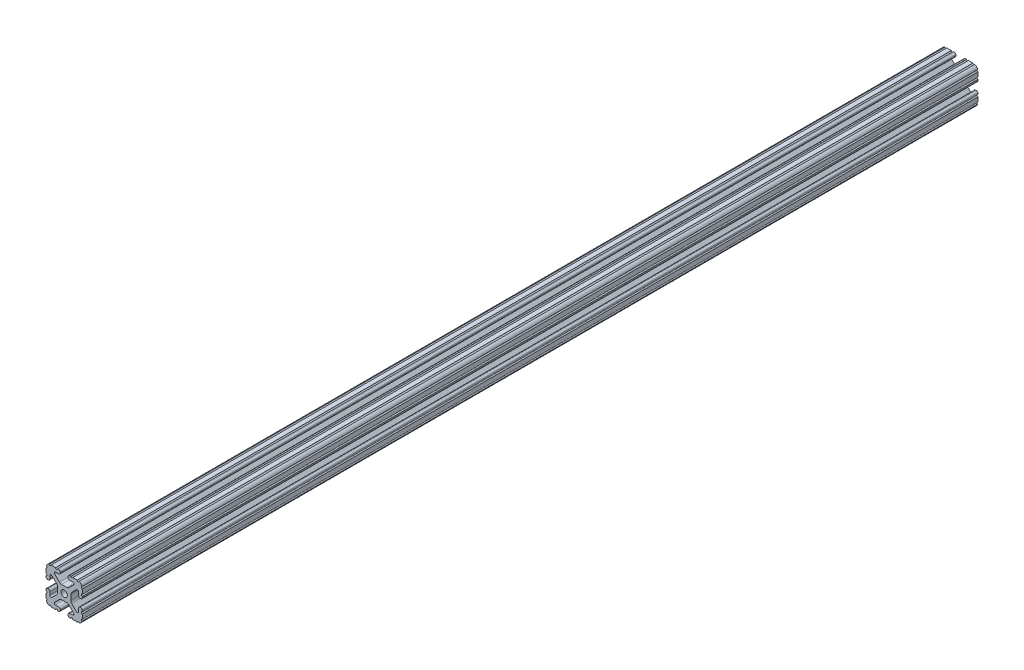
SolidWorks part; units mm, degrees
ref_plane "Front Plane" through (0, 0, 0) normal (0, 0, 1) x (1, 0, 0)
ref_plane "Top Plane" through (0, 0, 0) normal (0, 1, 0) x (1, 0, 0)
ref_plane "Right Plane" through (0, 0, 0) normal (1, 0, 0) x (0, 0, -1)
sketch "Sketch2" plane through (0, 0, 0) normal (0, 0, 1) x (1, 0, 0)
  line L0 (0, 19.05) -> (0, -19.05) construction
  line L1 (-19.05, 0) -> (19.05, 0) construction
  line L2 (4.064, -19.05) -> (19.05, -19.05)
  line L3 (19.05, -19.05) -> (19.05, -4.064)
  line L4 (4.064, -19.05) -> (4.064, -14.986)
  line L5 (4.064, -14.986) -> (12.1123, -14.986)
  line L6 (12.1123, -14.986) -> (4.1113, -6.985)
  line L7 (0, 0) -> (19.05, -19.05) construction
  line L8 (19.05, -4.064) -> (14.986, -4.064)
  line L9 (14.986, -4.064) -> (14.986, -12.1123)
  line L10 (14.986, -12.1123) -> (6.985, -4.1113)
  circle A0 centre (0, 0) radius 3.3274
  arc A1 (8.9963, -14.986) -> (9.909, -12.7826) centre (8.9963, -13.6953) ccw construction
  point P8 (0, -6.985)
  dimension "Center Hole Diameter" = 6.6548
  dimension "Rail Height" = 38.1
  dimension "Rail Width" = 38.1
  dimension "T-Slot Width" = 8.128
  dimension "Slot Inner Width" = 20.574
  dimension "Thickness" = 4.064
  dimension "Slot Depth" = 8.001
  dimension "D1" = 4.064
sketch "Sketch3" plane through (0, 0, 0) normal (1, 0, 0) x (0, 0, -1)
  line L0 (-469.9, -19.05) -> (469.9, -19.05) construction
  line L1 (-444.5, 0) -> (444.5, 0) construction
  dimension "Length" = 939.8
  dimension "D1" = 25.4
sketch "Sketch4" plane through (0, 0, 0) normal (0, 0, 1) x (1, 0, 0)
  line L0 (5.7912, -19.05) -> (14.3002, -19.05)
  line L1 (4.064, -19.05) -> (19.05, -19.05) construction
  line L2 (4.064, -19.05) -> (4.064, -14.986) construction
  line L3 (4.064, -14.986) -> (12.1123, -14.986) construction
  line L4 (4.064, -16.7132) -> (4.064, -17.3228)
  line L5 (5.7912, -14.986) -> (8.9963, -14.986)
  line L6 (0, -6.985) -> (2.833, -6.985)
  line L7 (12.1123, -14.986) -> (4.1113, -6.985) construction
  line L8 (5.0152, -7.8889) -> (9.909, -12.7826)
  line L9 (19.05, -19.05) -> (19.05, -4.064) construction
  line L10 (14.986, -12.1123) -> (6.985, -4.1113) construction
  line L11 (14.986, -4.064) -> (14.986, -12.1123) construction
  line L12 (14.986, -8.9963) -> (14.986, -5.7912)
  line L13 (19.05, -4.064) -> (14.986, -4.064) construction
  line L14 (16.7132, -4.064) -> (17.3228, -4.064)
  line L15 (19.05, -5.7912) -> (19.05, -14.3002)
  line L16 (12.7826, -9.909) -> (7.8889, -5.0152)
  line L17 (6.985, 0) -> (6.985, -2.833)
  line L18 (-19.05, 0) -> (19.05, 0) construction
  line L19 (0, -6.985) -> (0, -3.3274)
  line L20 (0, 19.05) -> (0, -19.05) construction
  line L21 (6.985, 0) -> (3.3274, 0)
  arc A0 (4.064, -17.3228) -> (5.7912, -19.05) centre (5.7912, -17.3228) ccw
  arc A2 (4.064, -16.7132) -> (5.7912, -14.986) centre (5.7912, -16.7132) cw
  arc A3 (8.9963, -14.986) -> (9.909, -12.7826) centre (8.9963, -13.6953) ccw
  arc A4 (2.833, -6.985) -> (5.0152, -7.8889) centre (2.833, -10.0711) cw
  arc A5 (14.3002, -19.05) -> (19.05, -14.3002) centre (14.3002, -14.3002) ccw
  arc A6 (12.7826, -9.909) -> (14.986, -8.9963) centre (13.6953, -8.9963) ccw
  arc A7 (14.986, -5.7912) -> (16.7132, -4.064) centre (16.7132, -5.7912) cw
  arc A8 (17.3228, -4.064) -> (19.05, -5.7912) centre (17.3228, -5.7912) cw
  arc A9 (7.8889, -5.0152) -> (6.985, -2.833) centre (10.0711, -2.833) cw
  circle A10 centre (0, 0) radius 3.3274 construction
  arc A11 (0, -3.3274) -> (3.3274, 0) centre (0, 0) ccw
  dimension "D1" = 4.7498
  dimension "D2" = 3.0861
  dimension "D3" = 1.7272
extrude "Boss-Extrude1" add sketch "Sketch4" along normal mid plane 939.8
sketch "Sketch5" plane through (0, 0, 0) normal (0, 0, 1) x (1, 0, 0)
  line L0 (4.064, -19.05) -> (19.05, -19.05) construction
  line L1 (5.7912, -14.986) -> (8.9963, -14.986) construction
  line L3 (0, 0) -> (19.05, -19.05) construction
  line L4 (8.9963, -14.986) -> (8.9963, -19.05) construction
  line L5 (12.1123, -14.986) -> (4.1113, -6.985) construction
  circle A0 centre (14.7395, -19.05) radius 1.016
  circle A1 centre (7.9803, -19.05) radius 1.016
  circle A2 centre (19.05, -14.7395) radius 1.016
  circle A3 centre (19.05, -7.9803) radius 1.016
  point P10 (7.3938, -14.986)
  point P12 (13.6953, -8.9963)
  dimension "D1" = 2.032
extrude "Cut-Extrude1" cut sketch "Sketch5" against normal through all both and the other way through all
mirror "Mirror1" about plane through (0, 0, 0) normal (1, 0, 0) of bodies 137 134
mirror "Mirror2" about plane through (0, 0, 0) normal (0, 1, 0) of bodies 135
equation "\"D1@Boss-Extrude1\"=\"Length@Sketch3\""
equation "\"D1@Sketch2\"=\"Thickness@Sketch2\""
equation "\"D2@Sketch4\"=\"Slot Inner Width@Sketch2\"*0.15"
equation "\"D1@Sketch4\"=\"D3@Sketch4\"*2.75"
equation "\"D3@Sketch4\"=\"Thickness@Sketch2\"*0.425"
equation "\"D1@Sketch5\"=\"Thickness@Sketch2\"*0.5"
